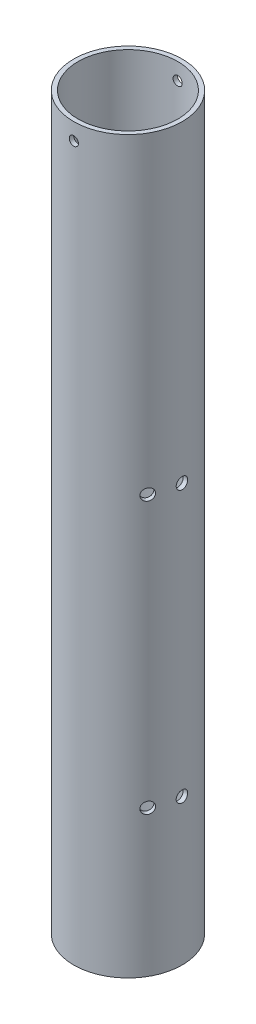
SolidWorks part; units mm, degrees
ref_plane "Front Plane" through (0, 0, 0) normal (0, 0, 1) x (1, 0, 0)
ref_plane "Top Plane" through (0, 0, 0) normal (0, 1, 0) x (1, 0, 0)
ref_plane "Right Plane" through (0, 0, 0) normal (1, 0, 0) x (0, 0, -1)
sketch "Sketch1" plane through (0, 0, 0) normal (0, 1, 0) x (1, 0, 0)
  circle A0 centre (0, 0) radius 26
  circle A1 centre (0, 0) radius 23.9
  dimension "D1" = 52
  dimension "D2" = 47.8
extrude "Boss-Extrude1" add sketch "Sketch1" along normal blind 350
sketch "Sketch3" plane through (0, 0, 0) normal (0, 0, 1) x (1, 0, 0)
  line L0 (0, 70) -> (0, 0)
  line L1 (0, 70) -> (0, 200)
  line L2 (-26, 0) -> (26, 0) construction
  circle A0 centre (0, 70) radius 2.75
  circle A1 centre (0, 200) radius 2.75
  dimension "D2" = 5.5
  dimension "D3" = 5.5
  dimension "D1" = 70
  dimension "D4" = 200
extrude "Cut-Extrude2" cut sketch "Sketch3" against normal through all
pattern_circular "CirPattern1" count 3 over 360 about axis through (0, 350, 0) along (0, -1, 0) of "Cut-Extrude2"
sketch "Sketch5" plane through (0, 0, 0) normal (1, 0, 0) x (0, 0, -1)
  line L0 (0, 70) -> (0, 0)
  line L1 (0, 70) -> (0, 200)
  circle A0 centre (0, 200) radius 2.75
  circle A1 centre (0, 70) radius 2.75
  dimension "D2" = 5.5
  dimension "D1" = 70
  dimension "D4" = 5.5
  dimension "D3" = 200
extrude "Cut-Extrude3" cut sketch "Sketch5" against normal through all both and the other way through all
sketch "Sketch6" plane through (0, 0, 0) normal (0, 0, 1) x (1, 0, 0)
  line L0 (23.9, 350) -> (-23.9, 350) construction
  line L1 (0, 350) -> (0, 342)
  circle A0 centre (0, 342) radius 2.1949
  dimension "D1" = 4.3898
  dimension "D2" = 8
extrude "Cut-Extrude4" cut sketch "Sketch6" against normal through all both and the other way through all
equation "\"TubeOutsideDiameter\"= 52"
equation "\"D1@Sketch1\"=\"TubeOutsideDiameter\""
equation "\"TubeInnerDiameter\"= 47.8"
equation "\"ReleaseMechanisumHeight\"=100"
equation "\"WireDiameter\"=3.38983"
equation "\"servoHoleDiameter\"= 2.8"
equation "\"CordDiameter\"= 5"
equation "\"MountingBoldDiameter\"=2.8"
equation "\"TubeMountingBoltDiameter\"= 5"
equation "\"D2@Sketch1\"=\"TubeInnerDiameter\""
equation "\"CardTubeOutsideDiameter\"= 54.2"
equation "\"CardTubeInsideDiameter\"= 50.4"
equation "\"D2@Sketch3\"=\"TubeMountingBoltDiameter\"+0.5"
equation "\"D3@Sketch3\"=\"TubeMountingBoltDiameter\"+0.5"
equation "\"D2@Sketch5\"=\"TubeMountingBoltDiameter\"+0.5"
equation "\"D4@Sketch5\"=\"TubeMountingBoltDiameter\"+0.5"
equation "\"D1@Sketch3\"=(\"ReleaseMechanisumHeight\"/2)+20"
equation "\"D1@Sketch5\"=(\"ReleaseMechanisumHeight\"/2)+20"
equation "\"D1@Sketch6\"=\"WireDiameter\"+1"
